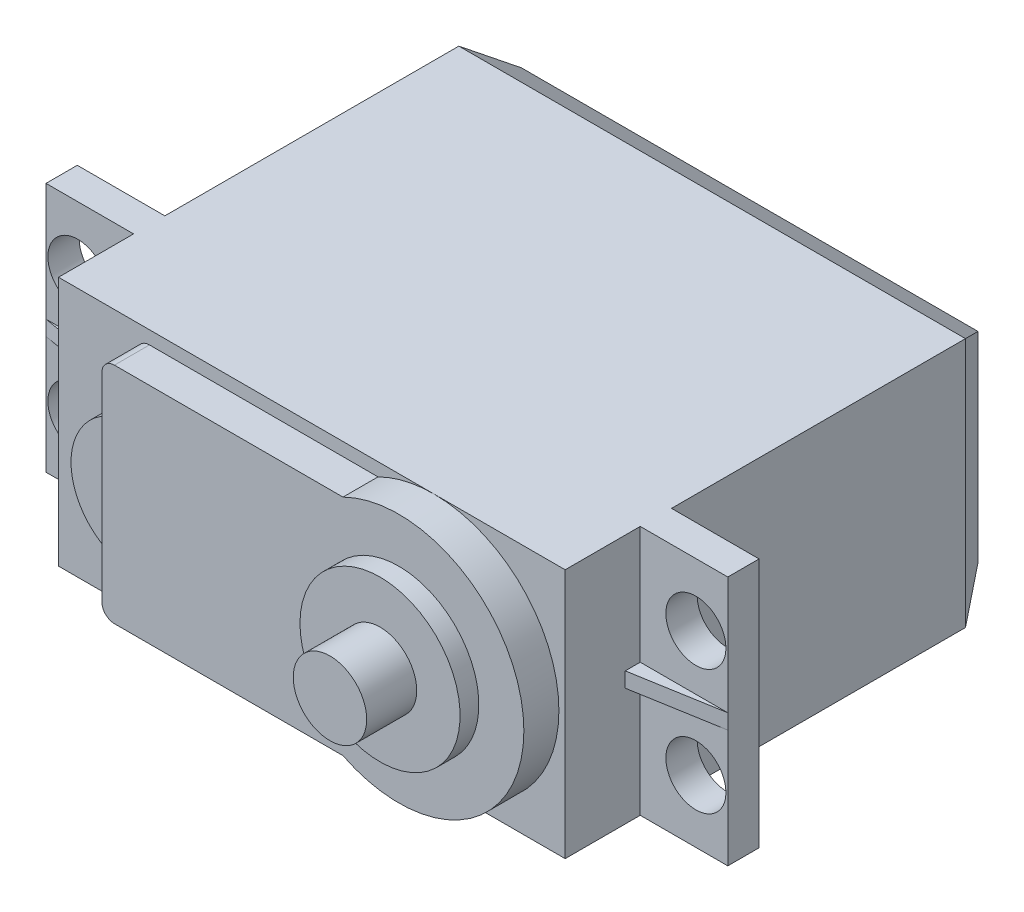
SolidWorks part; units mm, degrees
ref_plane "Front Plane" through (0, 0, 0) normal (0, 0, 1) x (1, 0, 0)
ref_plane "Top Plane" through (0, 0, 0) normal (0, 1, 0) x (1, 0, 0)
ref_plane "Right Plane" through (0, 0, 0) normal (1, 0, 0) x (0, 0, -1)
ref_plane "Plane1" through (0, 10, 0) normal (0, 1, 0) x (1, 0, 0)
sketch "Sketch1" plane through (0, 10, 0) normal (0, 1, 0) x (1, 0, 0)
  line L0 (27.25, -28.5) -> (27.25, 6.5)
  line L1 (27.25, 6.5) -> (-27.25, 6.5)
  line L2 (-27.25, 6.5) -> (-27.25, -28.5)
  line L3 (-27.25, -28.5) -> (27.25, -28.5)
extrude "Boss-Extrude1" add sketch "Sketch1" against normal blind 20
sketch "Sketch2" plane through (0, 0, 28.5) normal (0, 0, 1) x (1, 0, 0)
  line L0 (-13.98, 8.95) -> (5.2893, 8.95)
  line L1 (5.2893, -8.95) -> (-13.98, -8.95)
  line L2 (-13.98, -8.95) -> (-13.98, 8.95)
  arc A0 (5.2893, 8.95) -> (5.2893, -8.95) centre (9.75, 0) cw
extrude "Boss-Extrude2" add sketch "Sketch2" along normal blind 2.8
sketch "Sketch3" plane through (0, -10, 0) normal (0, -1, 0) x (1, 0, 0)
  line L0 (-20.25, -6.5) -> (-20.25, 20)
  line L1 (-20.25, 20) -> (-27.25, 20)
  line L2 (-27.25, 20) -> (-27.25, -6.5)
  line L3 (-27.25, -6.5) -> (-20.25, -6.5)
extrude "Cut-Extrude1" cut sketch "Sketch3" against normal through all
sketch "Sketch4" plane through (0, -10, 0) normal (0, -1, 0) x (1, 0, 0)
  line L0 (-20.25, 22.5) -> (-20.25, 28.5)
  line L1 (-20.25, 28.5) -> (-27.25, 28.5)
  line L2 (-27.25, 28.5) -> (-27.25, 22.5)
  line L3 (-27.25, 22.5) -> (-20.25, 22.5)
extrude "Cut-Extrude2" cut sketch "Sketch4" against normal through all
sketch "Sketch5" plane through (0, -10, 0) normal (0, -1, 0) x (1, 0, 0)
  line L0 (20.25, 28.5) -> (20.25, 22.5)
  line L1 (20.25, 22.5) -> (27.25, 22.5)
  line L2 (27.25, 22.5) -> (27.25, 28.5)
  line L3 (27.25, 28.5) -> (20.25, 28.5)
extrude "Cut-Extrude3" cut sketch "Sketch5" against normal through all
sketch "Sketch6" plane through (0, -10, 0) normal (0, -1, 0) x (1, 0, 0)
  line L0 (20.25, 20) -> (20.25, -6.5)
  line L1 (20.25, -6.5) -> (27.25, -6.5)
  line L2 (27.25, -6.5) -> (27.25, 20)
  line L3 (27.25, 20) -> (20.25, 20)
extrude "Cut-Extrude4" cut sketch "Sketch6" against normal through all
sketch "Sketch7" plane through (0, 0, 28.5) normal (0, 0, 1) x (1, 0, 0)
  line L0 (-13.98, 4.685) -> (-13.98, -4.685)
  arc A0 (-13.98, -4.685) -> (-13.98, 4.685) centre (-11.7698, 0) cw
extrude "Boss-Extrude3" add sketch "Sketch7" along normal blind 2.3
ref_plane "Plane2" through (0, 0, 0) normal (0, -1, 0) x (1, 0, 0)
sketch "Sketch8" plane through (0, 0, 0) normal (0, -1, 0) x (1, 0, 0)
  line L0 (12.685, 36.8) -> (9.75, 36.8)
  line L1 (9.75, 36.8) -> (9.75, 31.3)
  line L2 (9.75, 31.3) -> (16.15, 31.3)
  line L3 (16.15, 31.3) -> (16.15, 32.8)
  line L4 (16.15, 32.8) -> (12.685, 32.8)
  line L5 (12.685, 32.8) -> (12.685, 36.8)
  line L6 (9.75, 36.8) -> (9.75, 31.3) construction
revolve "Revolve1" add sketch "Sketch8" angle 360 about L6
hole_wizard "Ø4.8 (4.8) Diameter Hole1" positions "Sketch10" profile "Sketch9" hole size "Ø4.8" standard "ANSI Metric"
sketch "Sketch10" plane through (0, 0, 20) normal (0, 0, -1) x (-1, 0, 0)
  point P0 (-24.7, -5)
  point P1 (24.7, -5)
  point P2 (24.7, 5)
  point P3 (-24.7, 5)
sketch "Sketch9" plane through (24.7, -5, 20) normal (1, 0, 0) x (0, 1, 0)
  line L0 (0, 0) -> (0, 16.8)
  line L1 (0, 16.8) -> (2.4, 16.8)
  line L2 (2.4, 16.8) -> (2.4, 0)
  line L5 (2.4, 0) -> (0, 0)
  line L11 (0, -6.35) -> (0, 107.95) construction
  dimension "Thru Hole Dia." = 4.8
  dimension "Thru Hole Depth" = 16.8
sketch "Sketch11" plane through (0, 0, 0) normal (0, 1, 0) x (1, 0, 0)
  line L0 (20.25, -23.7) -> (27.25, -22.5)
rib "Rib1" sketch "Sketch11" sketch "Sketch11" thickness 1.2 extrusion direction parallel to sketch draft on no parameters "D1"=1.2
sketch "Sketch12" plane through (0, 0, 0) normal (0, 1, 0) x (1, 0, 0)
  line L0 (-27.25, -22.5) -> (-20.25, -23.7)
rib "Rib2" sketch "Sketch12" sketch "Sketch12" thickness 1.2 extrusion direction parallel to sketch draft on no parameters "D1"=1.2
chamfer "Chamfer1" distance 2 angle 56.31 4 edges at (20.25, 0, -6.5) (0, 10, -6.5) (0, -10, -6.5) (-20.25, 0, -6.5)
fillet "Fillet1" radius 1 2 edges at (-13.98, -8.95, 29.9) (-13.98, 8.95, 29.9)
